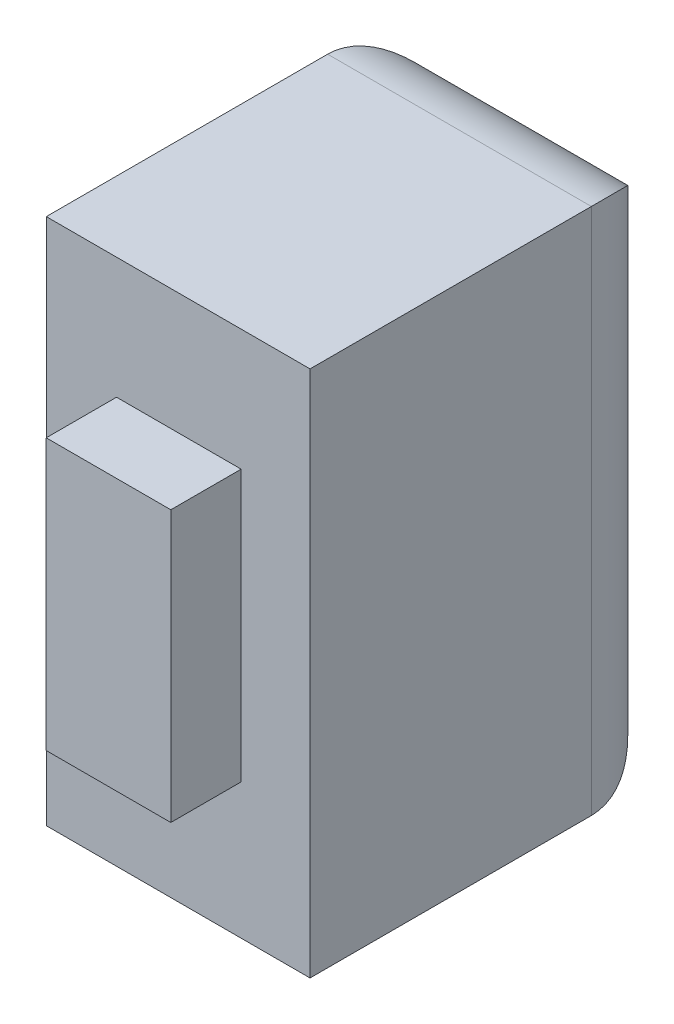
SolidWorks part; units mm, degrees
ref_plane "前视基准面" through (0, 0, 0) normal (0, 0, 1) x (1, 0, 0)
ref_plane "上视基准面" through (0, 0, 0) normal (0, 1, 0) x (1, 0, 0)
ref_plane "右视基准面" through (0, 0, 0) normal (1, 0, 0) x (0, 0, -1)
other "Configuration Table"
sketch "草图3" plane through (0, 0, 0) normal (0, 0, 1) x (1, 0, 0)
  line L1 (-2.0385, 1.183) -> (0.9615, 1.183)
  line L2 (-2.0385, 1.183) -> (-2.0385, -4.817)
  line L3 (-2.0385, -4.817) -> (0.9615, -4.817)
  line L4 (0.9615, 1.183) -> (0.9615, -4.817)
  dimension "D1" = 3
  dimension "D2" = 6
extrude "凸台-拉伸2" add sketch "草图3" along normal blind 3.5
sketch "草图4" plane through (0, 0, 3.5) normal (0, 0, 1) x (1, 0, 0)
  line L1 (-1.2395, -0.1964) -> (0.1779, -0.1964)
  line L2 (-1.2395, -0.1964) -> (-1.2395, -3.2769)
  line L3 (-1.2395, -3.2769) -> (0.1779, -3.2769)
  line L4 (0.1779, -0.1964) -> (0.1779, -3.2769)
extrude "切除-拉伸1" cut sketch "草图4" against normal blind 0.8 flip side to cut
sketch "草图9" plane through (0, 0, 0) normal (0, 0, -1) x (-1, 0, 0)
  line L5 (-0.9615, 1.183) -> (2.0385, 1.183)
  line L6 (-0.9615, 1.183) -> (-0.9615, -4.817)
  line L7 (-0.9615, -4.817) -> (2.0385, -4.817)
  line L8 (2.0385, 1.183) -> (2.0385, -4.817)
extrude "凸台-拉伸5" add sketch "草图9" along normal blind 1.5
fillet "圆角2" radius 1 4 edges at (-0.5385, 1.183, -1.5) (-0.5385, -4.817, -1.5) (-2.0385, -1.817, -1.5) (0.9615, -1.817, -1.5)
ref_plane "基准面1" through (-2.0385, 1.183, -0.5) normal (0, 0, -1) x (-1, 0, 0)
